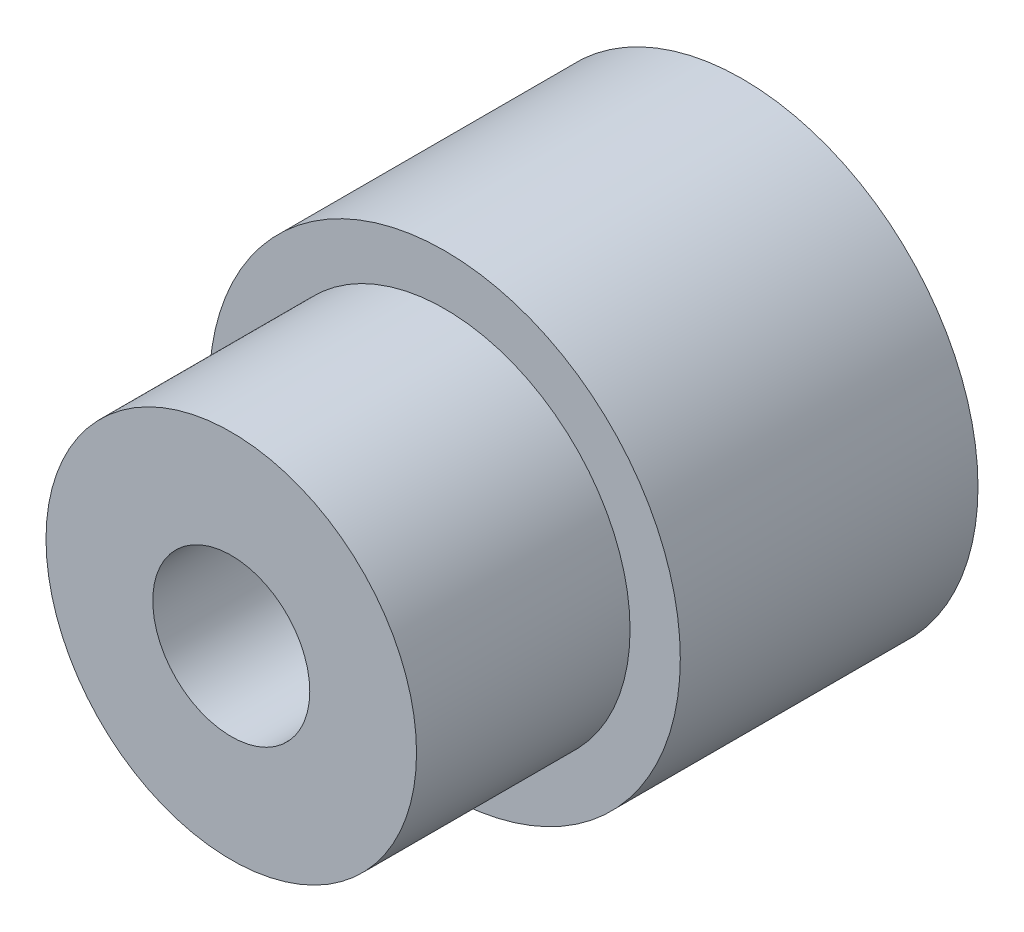
SolidWorks part; units mm, degrees
material "Plain Carbon Steel"
ref_plane "Front Plane" through (0, 0, 0) normal (0, 0, 1) x (1, 0, 0)
ref_plane "Top Plane" through (0, 0, 0) normal (0, 1, 0) x (1, 0, 0)
ref_plane "Right Plane" through (0, 0, 0) normal (1, 0, 0) x (0, 0, -1)
sketch "Sketch1" plane through (0, 0, 0) normal (0, 0, 1) x (1, 0, 0)
  circle A1 centre (0, 0) radius 4.7625
  dimension "D2" = 9.525
extrude "Boss-Extrude1" add sketch "Sketch1" along normal blind 6.0198
sketch "Sketch2" plane through (0, 0, 6.0198) normal (0, 0, 1) x (1, 0, 0)
  circle A0 centre (0, 0) radius 3.7465
  dimension "D1" = 7.493
extrude "Boss-Extrude2" add sketch "Sketch2" along normal blind 4.318
sketch "Sketch3" plane through (0, 0, 10.3378) normal (0, 0, 1) x (1, 0, 0)
  circle A0 centre (0, 0) radius 1.5875
  dimension "D1" = 3.175
extrude "Cut-Extrude1" cut sketch "Sketch3" against normal through all
